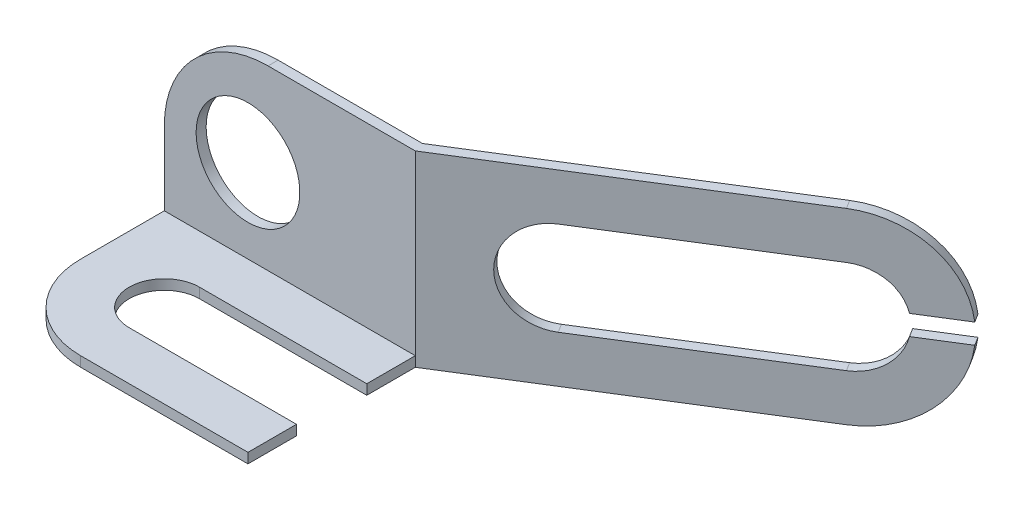
SolidWorks part; units mm, degrees
ref_plane "Front Plane" through (0, 0, 0) normal (0, 0, 1) x (1, 0, 0)
ref_plane "Top Plane" through (0, 0, 0) normal (0, 1, 0) x (1, 0, 0)
ref_plane "Right Plane" through (0, 0, 0) normal (1, 0, 0) x (0, 0, -1)
sketch "Sketch1" plane through (0, 0, 0) normal (0, 1, 0) x (1, 0, 0)
  line L0 (-0.25, 0) -> (1.2021, 0) construction
  line L1 (-0.75, 0.5) -> (0.75, 0.5)
  line L2 (-0.75, 0.5) -> (-0.75, 0)
  line L3 (-0.25, -0.5) -> (0.75, -0.5)
  line L4 (0.75, 0.5) -> (0.75, 0.21)
  line L5 (-0.75, 0.5) -> (0.75, -0.5) construction
  line L6 (-0.75, -0.5) -> (0.75, 0.5) construction
  line L7 (-0.25, 0.21) -> (0.75, 0.21)
  line L8 (-0.25, -0.21) -> (0.75, -0.21)
  line L9 (0.75, -0.21) -> (0.75, -0.5)
  arc A0 (-0.25, -0.5) -> (-0.75, 0) centre (-0.25, 0) cw
  arc A1 (-0.25, 0.21) -> (-0.25, -0.21) centre (-0.25, 0) ccw
  point P0 (0, 0)
  point P11 (0.476, 0)
  dimension "D3" = 0.5
  dimension "D5" = 0.21
  dimension "D1" = 1
  dimension "D2" = 1.5
  dimension "D4" = 0.5
extrude "Boss-Extrude1" add sketch "Sketch1" along normal blind 0.06
sketch "Sketch3" plane through (0, 0, -0.5) normal (0, 0, -1) x (-1, 0, 0)
  line L0 (-0.75, 0.06) -> (0.75, 0.06) construction
  line L1 (-0.75, 0) -> (0.75, 0)
  line L2 (-0.75, 0) -> (-0.75, 1.12)
  line L3 (-0.75, 1.12) -> (0.13, 1.12)
  line L4 (0.75, 0) -> (0.75, 0.5)
  arc A0 (0.75, 0.5) -> (0.13, 1.12) centre (0.13, 0.5) ccw
  circle A1 centre (0.25, 0.56) radius 0.31
  dimension "D3" = 0.62
  dimension "D4" = 0.62
  dimension "D1" = 1.12
  dimension "D2" = 1.5
  dimension "D5" = 0.5
  dimension "D6" = 0.5
extrude "Boss-Extrude2" add sketch "Sketch3" along normal blind 0.06
sketch "Sketch5" plane through (0, 0.06, 0) normal (0, 1, 0) x (1, 0, 0)
  line L0 (0.75, 0.5) -> (1.4399, 0.9311) construction
  line L2 (-0.13, 0.5) -> (0.75, 0.5) construction
  dimension "D1" = 32
ref_plane "Plane1" through (-0.0141, 0, -0.0225) normal (-0.5299, 0, -0.848) x (-0.848, 0, 0.5299)
sketch "Sketch6" plane through (-0.0141, 0, -0.0225) normal (-0.5299, 0, -0.848) x (-0.848, 0, 0.5299)
  line L0 (-1.7075, 0.56) -> (-2.771, 0.56) construction
  line L1 (-0.901, 1.12) -> (-2.771, 1.12)
  line L2 (-0.901, 1.12) -> (-0.901, 0)
  line L3 (-0.901, 0) -> (-2.771, 0)
  line L5 (-1.521, 0.28) -> (-2.771, 0.28)
  line L6 (-1.521, 0.84) -> (-2.771, 0.84)
  line L8 (-3.0445, 0.5) -> (-3.3278, 0.5)
  line L10 (-3.0445, 0.62) -> (-3.3278, 0.62)
  line L12 (-1.7605, 0.5) -> (-2.771, 0.56) construction
  arc A0 (-2.771, 1.12) -> (-3.3278, 0.62) centre (-2.771, 0.56) ccw
  arc A1 (-1.521, 0.28) -> (-1.521, 0.84) centre (-1.521, 0.56) ccw
  arc A2 (-2.771, 0.84) -> (-3.0445, 0.62) centre (-2.771, 0.56) ccw
  arc A3 (-3.0445, 0.5) -> (-2.771, 0.28) centre (-2.771, 0.56) ccw
  arc A4 (-3.3278, 0.5) -> (-2.771, 0) centre (-2.771, 0.56) ccw
  point P8 (-2.146, 0.56)
  point P13 (-2.771, 0.56)
  dimension "D4" = 0.28
  dimension "D1" = 1.12
  dimension "D3" = 1.25
  dimension "D5" = 0.62
extrude "Boss-Extrude3" add sketch "Sketch6" along normal blind 0.06
